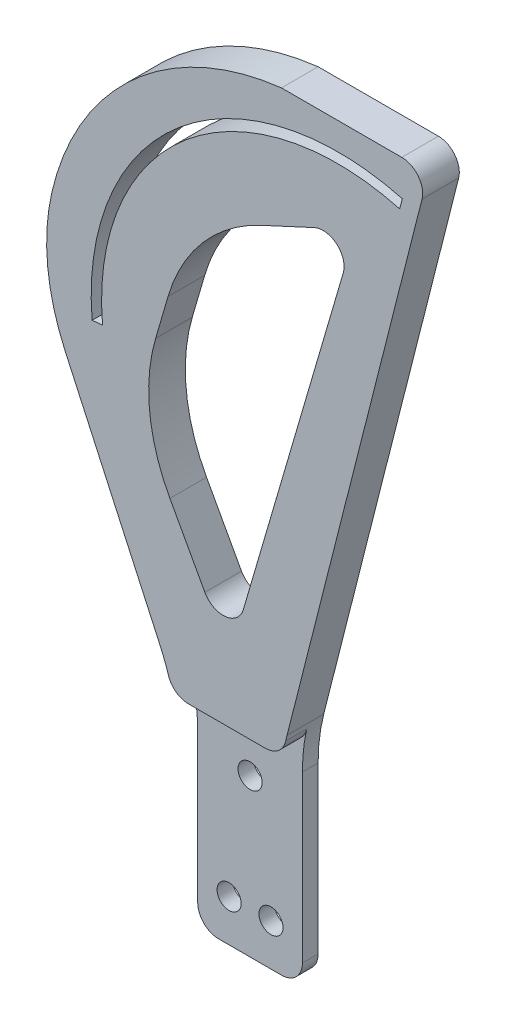
SolidWorks part; units mm, degrees
ref_plane "Front Plane" through (0, 0, 0) normal (0, 0, 1) x (1, 0, 0)
ref_plane "Top Plane" through (0, 0, 0) normal (0, 1, 0) x (1, 0, 0)
ref_plane "Right Plane" through (0, 0, 0) normal (1, 0, 0) x (0, 0, -1)
sketch "Sketch1" plane through (0, 0, 0) normal (0, 0, 1) x (1, 0, 0)
  line L0 (-10, 0) -> (-10, 40)
  line L1 (24.2736, 134.5199) -> (0, 51.5556)
  line L2 (32.5815, 142.0692) -> (33.0979, 144.0013)
  line L3 (-10, 0) -> (10, 0)
  line L4 (-26.1752, 94.2653) -> (-24.1827, 94.4383)
  line L5 (10, 150.7971) -> (38.123, 150.7971)
  line L6 (38.123, 150.7971) -> (10, 40)
  line L7 (10, 40) -> (10, 0)
  line L8 (-34.8351, 94.2653) -> (-10, 40)
  line L9 (0, 51.5556) -> (-17.8773, 84.2205)
  line L10 (-17.8773, 84.2205) -> (-7.4576, 119.8337)
  line L11 (-7.4576, 119.8337) -> (24.2736, 134.5199)
  circle A0 centre (0, 30) radius 2.3
  circle A1 centre (4, 8) radius 2.3
  circle A2 centre (-4, 8) radius 2.3
  arc A3 (33.0979, 144.0013) -> (-26.1752, 94.2653) centre (20.8976, 98.3536) ccw
  arc A4 (32.5815, 142.0692) -> (-24.1827, 94.4383) centre (20.7611, 98.5163) ccw
  arc A5 (10, 150.7971) -> (-34.8351, 94.2653) centre (15.8484, 100.1137) ccw
  point P0 (-10, 0)
  point P1 (10, 0)
  point P2 (4, 8)
  point P3 (-4, 8)
  point P4 (10, 40)
  point P5 (-10, 40)
  point P6 (0, 30)
  point P23 (32.5815, 142.0692)
  point P24 (-24.1827, 94.4383)
extrude "Extrude1" add sketch "Sketch1" along normal blind 7
fillet "Fillet1" radius 39 1 edges at (-34.8351, 94.2653, 3.5)
fillet "Fillet2" radius 33 2 edges at (-17.8773, 84.2205, 3.5) (-7.4576, 119.8337, 3.5)
fillet "Fillet3" radius 4 5 edges at (-10, 0, 3.5) (10, 0, 3.5) (0, 51.5556, 3.5) (24.2736, 134.5199, 3.5) (38.123, 150.7971, 3.5)
fillet "Fillet4" radius 35 2 edges at (-10, 40, 3.5) (10, 40, 3.5)
sketch "Sketch2" plane through (0, 0, 7) normal (0, 0, 1) x (1, 0, 0)
  line L1 (16.3558, 0) -> (-16.5899, 0)
  line L2 (16.3558, 0) -> (16.3558, 40)
  line L3 (16.3558, 40) -> (-16.5899, 40)
  line L4 (-16.5899, 0) -> (-16.5899, 40)
extrude "Cut-Extrude1" cut sketch "Sketch2" against normal blind 4
fillet "Fillet5" radius 4 2 edges at (-10.8415, 40, 5) (10.2742, 40, 5)
